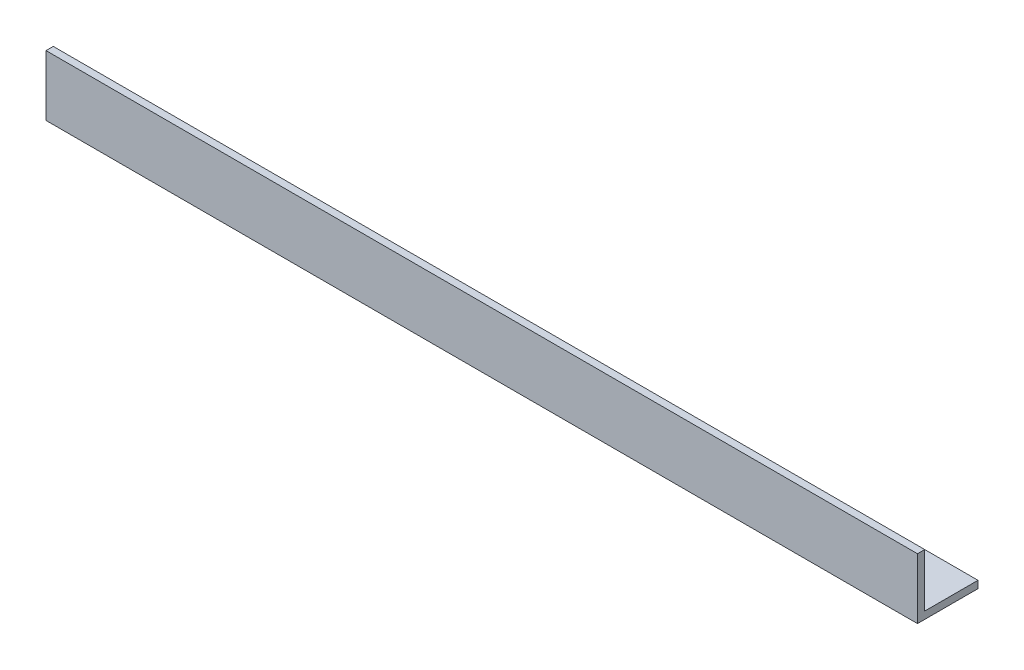
SolidWorks part; units mm, degrees
ref_plane "前视基准面" through (0, 0, 0) normal (0, 0, 1) x (1, 0, 0)
ref_plane "上视基准面" through (0, 0, 0) normal (0, 1, 0) x (1, 0, 0)
ref_plane "右视基准面" through (0, 0, 0) normal (1, 0, 0) x (0, 0, -1)
sketch "Sketch1" plane through (0, 0, 0) normal (1, 0, 0) x (0, 0, -1)
  line L0 (0, 22) -> (0, 0)
  line L1 (0, 0) -> (22, 0)
  line L2 (22, 0) -> (22, -3)
  line L3 (22, -3) -> (-3, -3)
  line L4 (-3, -3) -> (-3, 22)
  line L5 (-3, 22) -> (0, 22)
  dimension "D1" = 3
  dimension "D2" = 3
  dimension "D3" = 25
  dimension "D4" = 25
extrude "Boss-Extrude1" add sketch "Sketch1" along normal mid plane 360
sketch "Sketch2" plane through (0, 0, 0) normal (0, 1, 0) x (1, 0, 0)
  line L0 (-180, 11) -> (180, 11) construction
  line L1 (-180, 22) -> (-180, 0) construction
  line L2 (180, 22) -> (180, 0) construction
  circle A0 centre (-160, 11) radius 2.75
  circle A1 centre (-120, 11) radius 2.75
  circle A2 centre (-80, 11) radius 2.75
  circle A3 centre (-40, 11) radius 2.75
  circle A4 centre (0, 11) radius 2.75
  circle A5 centre (40, 11) radius 2.75
  circle A6 centre (80, 11) radius 2.75
  circle A7 centre (120, 11) radius 2.75
  circle A8 centre (160, 11) radius 2.75
  dimension "D1" = 5.5
  dimension "D2" = 20
  dimension "D4" = 40
  dimension "D3" = 9
extrude "Cut-Extrude1" cut sketch "Sketch2" against normal through all both and the other way through all
